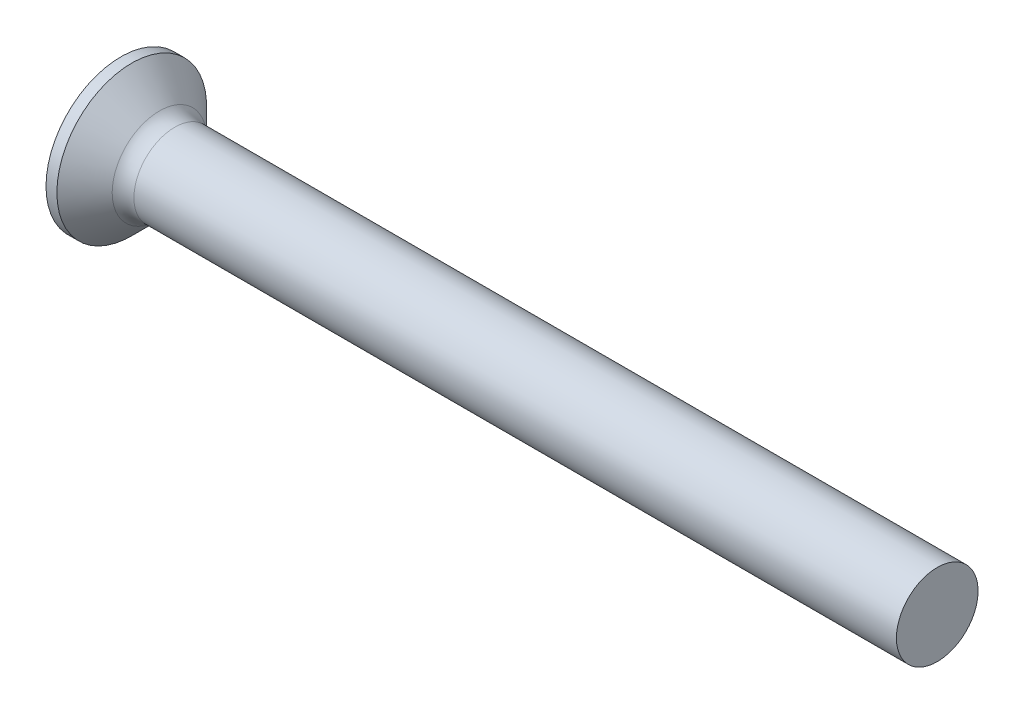
SolidWorks part; units mm, degrees
revolve "Base-Revolve" add sketch "BodySke"
sketch "BodySke" plane through (0, 0, 0) normal (0, 0, 1) x (1, 0, 0)
  line L0 (0, 0) -> (0, 2.75)
  line L1 (0, 2.75) -> (0.4, 2.75)
  line L2 (1.65, 1.5) -> (30, 1.5)
  line L3 (30, 1.5) -> (30, 0)
  line L4 (30, 0) -> (0, 0)
  line L5 (-6.35, 0) -> (82.55, 0) construction
  line L6 (1.65, -1.5) -> (30, -1.5) construction
  line L7 (0.4, -2.75) -> (1.65, -1.5) construction
  line L8 (0.4, 2.75) -> (1.65, 1.5)
  line L9 (0, -2.75) -> (0.4, -2.75) construction
  line L10 (2.15, 3.0875) -> (2.15, -6.4375) construction
  line L11 (0, 6.35) -> (0, -3.175) construction
  dimension "Head_ang" = 90
  dimension "D6" = 0.4
cosmetic thread "ThreadCosmetic" [suppressed]
fillet "Fillet1" radius 0.8 1 edges at (1.65, 0, 1.5)
ref_plane "Plane1" through (0, 0, 0) normal (0, 0, 1) x (1, 0, 0)
ref_plane "Plane2" through (0, 0, 0) normal (0, 1, 0) x (1, 0, 0)
ref_plane "Plane3" through (0, 0, 0) normal (1, 0, 0) x (0, 0, -1)
other "Configuration Table"
sketch "Sketch3" plane through (0, 0, 0) normal (-1, 0, 0) x (0, 0, 1)
  line L0 (-0.37, 1.5) -> (0.37, 1.5)
  line L1 (0.37, 1.5) -> (0.37, -1.5)
  line L2 (0.37, -1.5) -> (-0.37, -1.5)
  line L3 (-0.37, -1.5) -> (-0.37, 1.5)
  dimension "Cross_width" = 0.74
  dimension "D2" = 0.37
ref_plane "Plane4" through (2.01, 0, 0) normal (-1, 0, 0) x (0, 0, 1)
sketch "Sketch4" plane through (2.01, 0, 0) normal (-1, 0, 0) x (0, 0, 1)
  line L0 (-0.37, 0.4979) -> (0.37, 0.4979)
  line L3 (0.37, 0.4979) -> (0.37, -0.4979)
  line L4 (0.37, -0.4979) -> (-0.37, -0.4979)
  line L5 (-0.37, -0.4979) -> (-0.37, 0.4979)
  dimension "D1" = 0.74
  dimension "D3" = 0.37
loft "Recess" cut profiles "Sketch3", "Sketch4"
pattern_circular "RecPat" count 2 every 90 about axis through (0, 0, 0) along (1, 0, 0) of "Recess"
sketch "RecCorSke" plane through (0, 0, 0) normal (0, 0, 1) x (1, 0, 0)
  line L0 (-3.175, 0) -> (15.875, 0) construction
  line L2 (0, 0) -> (0, 0.6966)
  line L3 (0, 0.6966) -> (2.01, 0.556)
  line L4 (2.01, 0.556) -> (2.1907, 0)
  line L5 (2.1907, 0) -> (0, 0)
  dimension "Diameter" = 1.112
  dimension "Draft_angle" = 4
  dimension "Bottom_angle" = 18
revolve "RecessCore" cut sketch "RecCorSke" angle 360 about L0
sketch "ThdSchSke" plane through (0, 0, 0) normal (0, 0, 1) x (1, 0, 0)
  line L0 (2.15, -1.2195) -> (1.9536, -1.5)
  line L1 (2.15, -1.2195) -> (2.3464, -1.5)
  line L2 (2.3464, -1.5) -> (2.3464, -1.875)
  line L3 (-3.175, 0) -> (5.1513, 0) construction
  line L5 (2.3464, -1.875) -> (1.9536, -1.875)
  line L6 (1.9536, -1.875) -> (1.9536, -1.5)
  line L7 (0, 2.75) -> (0, -2.75) construction
revolve "ThreadSchematic" [suppressed] cut sketch "ThdSchSke" angle 360 about L3
pattern_linear "ThdSchPat" [suppressed]
equation "\"D1@Sketch3\" = \"Cross_dia@Sketch3\" / 2"
equation "\"D2@Sketch3\" = \"Cross_width@Sketch3\" / 2"
equation "\"Depth@RecCorSke\" = \"Cross_depth@Plane4\""
equation "\"D1@Sketch4\" = \"Cross_width@Sketch3\""
equation "\"D2@Sketch4\" = \"Cross_dia@Sketch3\" - 2.0 * \"Cross_depth@Plane4\" * tan(26.5  * 0.017453292)"
equation "\"D3@Sketch4\" = \"D1@Sketch4\" / 2"
equation "\"D4@Sketch4\" = \"D2@Sketch4\" / 2"
equation "\"Thread_length@ThreadCosmetic\" = ((sgn( (\"Length@BodySke\" - \"Advance@BodySke\" * 1.0 - \"Head_ht@BodySke\" ) - \"Thread_nom@BodySke\" )-1)*( (\"Length@BodySke\" - \"Advance@BodySke\" * 1.0 - \"Head_ht@BodySke\" ) - \"Thread_nom@BodySke\" ))/-2+ \"Thread_nom@BodySke\""
equation "\"Thread_minor@ThdSchSke\" = \"Thread_minor@ThreadCosmetic\""
equation "\"Diameter@ThdSchSke\" = \"Diameter@BodySke\""
equation "\"Overcut@ThdSchSke\" = \"Diameter@BodySke\" * 1.25"
equation "\"Start@ThdSchSke\" = 0.000001 + \"Length@BodySke\" - \"Thread_length@ThreadCosmetic\"  '---Countersunk---"
equation "\"Num_threads@ThdSchPat\" = int( \"Thread_length@ThreadCosmetic\" / \"Advance@BodySke\" + 0.999 )  + 1"
equation "\"Advance@ThdSchPat\" = \"Thread_length@ThreadCosmetic\" /  (\"Num_threads@ThdSchPat\" - 1) 'relax it"
